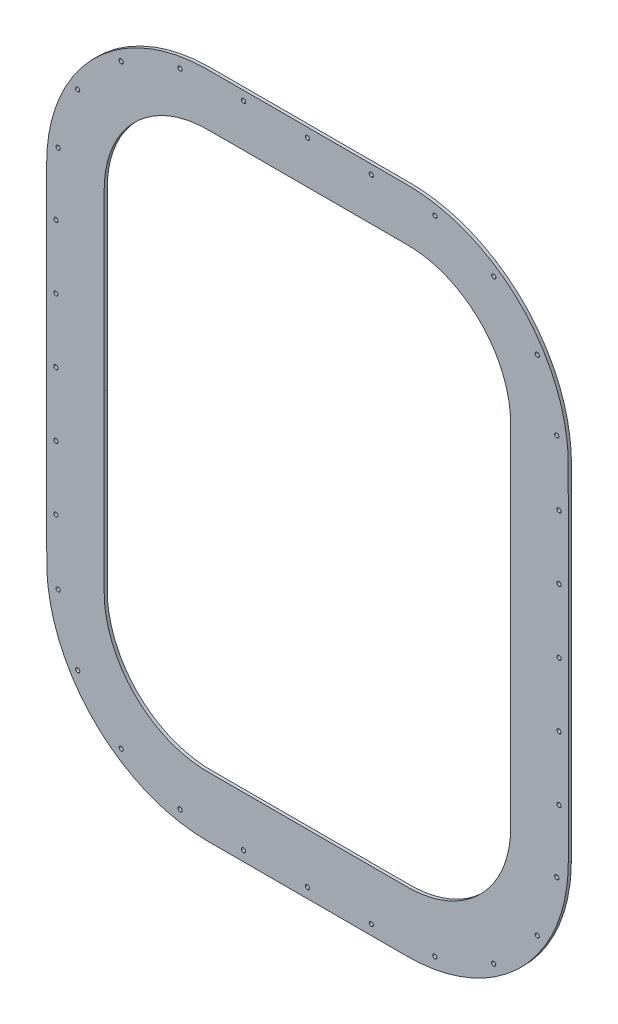
SolidWorks part; units mm, degrees
material "Сталь 3 ГОСТ 535-88"
ref_plane "Спереди" through (0, 0, 0) normal (0, 0, 1) x (1, 0, 0)
ref_plane "Сверху" through (0, 0, 0) normal (0, 1, 0) x (1, 0, 0)
ref_plane "Справа" through (0, 0, 0) normal (1, 0, 0) x (0, 0, -1)
sketch "Model" plane through (0, 0, 0) normal (0, 0, 1) x (1, 0, 0)
  spline S0 degree 3 poles (686.799, 219.4351) (686.8015, 233.7108) (686.7998, 247.9865) (686.7997, 276.538) (686.8001, 290.8137) (686.8001, 333.6409) (686.8, 362.1924) (686.8, 447.8467) (686.8, 504.9496) (686.8, 590.6192) (686.8, 619.1859) (686.8, 654.8942) (686.8031, 662.0359) (686.7984, 670.963) (686.7772, 672.7483) (686.6859, 676.3179) (686.6176, 678.1016) (686.3445, 683.4508) (686.0721, 687.0068) (684.2566, 704.7686) (681.3622, 718.7938) (672.7865, 746.0434) (667.1263, 759.1999) (653.2412, 784.1667) (645.0502, 795.9162) (626.4244, 817.5797) (616.051, 827.4251) (593.4407, 844.8927) (581.2722, 852.4548) (555.5632, 865.0005) (542.0668, 869.9511) (514.3076, 877.0039) (500.0892, 879.0962) (483.9931, 879.7895) (482.1463, 879.844) (478.691, 879.9047) (477.6323, 879.9057) (472.8047, 879.9051) (468.9033, 879.9055) (458.1634, 879.9055) (451.0035, 879.9055) (429.5236, 879.9055) (415.2037, 879.9055) (343.6042, 879.9055) (286.3245, 879.9057) (225.4722, 879.9053) (221.8995, 879.9052) (217.4336, 879.9052) (216.5404, 879.9081) (214.754, 879.8967) (213.8609, 879.8868) (211.1818, 879.8376) (209.3968, 879.7818) (200.4734, 879.3883) (193.3624, 878.7075) (172.1561, 875.5723) (158.2907, 872.0411) (131.4585, 862.1954) (118.6004, 855.9213) (94.3223, 840.8413) (82.9733, 832.0742) (62.2448, 812.4008) (52.9194, 801.5528) (36.5772, 778.11) (29.6245, 765.6091) (18.3314, 739.3598) (14.0339, 725.7079) (8.2593, 697.7226) (6.7982, 683.4477) (6.8, 669.1598) knots 1370.973405 1370.973405 1370.973405 1370.973405 1413.740122 1413.740122 1456.506838 1456.506838 1542.040272 1542.040272 1713.107139 1713.107139 1798.686145 1798.686145 1820.080897 1820.080897 1825.429585 1825.429585 1830.778273 1830.778273 1841.475649 1841.475649 1884.265152 1884.265152 1927.054655 1927.054655 1969.844159 1969.844159 2012.633662 2012.633662 2055.423165 2055.423165 2098.311408 2098.311408 2141.19965 2141.19965 2146.56068 2146.56068 2151.92171 2151.92171 2162.643771 2162.643771 2184.087892 2184.087892 2226.976134 2226.976134 2398.529103 2398.529103 2409.229434 2409.229434 2411.904516 2411.904516 2414.579599 2414.579599 2419.929764 2419.929764 2441.330424 2441.330424 2484.131745 2484.131745 2526.933066 2526.933066 2569.734386 2569.734386 2612.535707 2612.535707 2655.337028 2655.337028 2698.138349 2698.138349 2740.939669 2740.939669 2740.939669 2740.939669
  spline S1 degree 3 poles (6.8, 669.1598) (6.8, 554.954) (6.8, 440.7482) (6.8, 297.972) (6.8, 269.4017) (6.8, 237.26) (6.8, 233.6888) (6.8, 226.5462) (6.7988, 222.9747) (6.8026, 212.2613) (7.1617, 205.164) (9.3357, 183.8461) (12.2333, 169.7902) (20.8083, 142.5359) (26.4699, 129.3715) (36.8868, 110.6446) (40.6512, 104.6162) (48.8216, 92.8964) (53.1762, 87.2796) (67.1477, 71.029) (77.5232, 61.1824) (100.1392, 43.7149) (112.3204, 36.1477) (138.0408, 23.6044) (151.5435, 18.6552) (172.3727, 13.3683) (179.3623, 11.9714) (193.5364, 9.8881) (200.6319, 9.2149) (209.5782, 8.8278) (211.423, 8.7729) (214.887, 8.7115) (215.9044, 8.7107) (220.6306, 8.7119) (224.5877, 8.7112) (235.3325, 8.7112) (242.4957, 8.7111) (263.9853, 8.7111) (278.3117, 8.7111) (349.9438, 8.7112) (407.2494, 8.7111) (468.1373, 8.7112) (471.7389, 8.7113) (477.083, 8.7112) (478.2131, 8.7089) (481.4412, 8.7566) (483.3653, 8.8063) (492.3136, 9.1648) (499.4157, 9.8165) (513.5935, 11.855) (520.5935, 13.2309) (534.4875, 16.7129) (541.3096, 18.799) (561.5076, 26.125) (574.4387, 32.3811) (598.8267, 47.4238) (610.2201, 56.1755) (631.0536, 75.8455) (640.4448, 86.7245) (656.8705, 110.1985) (663.8805, 122.7636) (675.224, 149.072) (679.5476, 162.7829) (683.8928, 183.8251) (684.9779, 190.8681) (686.0714, 201.5552) (686.3445, 205.1215) (686.6183, 210.4861) (686.6868, 212.2748) (686.7781, 215.8547) (686.7987, 217.6446) (686.799, 219.4351) knots 0 0 0 0 342.110544 342.110544 427.694748 427.694748 438.392773 438.392773 449.090799 449.090799 470.48685 470.48685 513.278952 513.278952 556.071054 556.071054 577.467105 577.467105 598.863156 598.863156 641.655258 641.655258 684.44736 684.44736 727.351485 727.351485 748.803548 748.803548 770.25561 770.25561 775.618626 775.618626 780.981642 780.981642 791.707673 791.707673 813.159736 813.159736 856.063861 856.063861 1027.680361 1027.680361 1038.408269 1038.408269 1043.772223 1043.772223 1049.136177 1049.136177 1070.591992 1070.591992 1092.047807 1092.047807 1113.503622 1113.503622 1156.415253 1156.415253 1199.326883 1199.326883 1242.238514 1242.238514 1285.150144 1285.150144 1328.061775 1328.061775 1349.51759 1349.51759 1360.245497 1360.245497 1365.609451 1365.609451 1370.973405 1370.973405 1370.973405 1370.973405
  spline S2 degree 3 poles (611.8, 449.6949) (611.8, 402.1791) (611.8, 354.6634) (611.8, 283.3897) (611.8, 259.6319) (611.8, 232.9043) (611.8002, 229.9345) (611.7999, 225.4799) (611.8005, 223.9711) (611.7999, 221.0539) (611.7874, 219.8135) (611.5749, 212.401) (611.0155, 206.4829) (608.1729, 188.8911) (604.7349, 177.4448) (594.9606, 155.786) (588.6331, 145.6039) (577.3273, 131.8275) (573.2667, 127.4953) (564.5829, 119.3849) (559.9596, 115.6052) (550.2827, 108.7093) (545.2167, 105.5808) (534.7169, 100.0186) (529.297, 97.5903) (512.5842, 91.393) (500.9193, 88.7413) (486.1267, 87.389) (483.1216, 87.2163) (478.736, 87.106) (477.5663, 87.099) (474.6472, 87.101) (473.1376, 87.1002) (465.7105, 87.1009) (459.7689, 87.1004) (441.944, 87.1002) (430.0608, 87.1004) (394.411, 87.1004) (370.6445, 87.1004) (323.1405, 87.1004) (299.4031, 87.1004) (263.7969, 87.1004) (251.9282, 87.1003) (234.1251, 87.1003) (228.1907, 87.1003) (220.7727, 87.1006) (219.2891, 87.1007) (217.0638, 87.1006) (216.322, 87.0984) (214.8384, 87.1134) (214.0967, 87.1253) (210.3888, 87.2203) (207.4327, 87.3932) (192.658, 88.7484) (181.014, 91.3926) (164.321, 97.5832) (158.8788, 100.0193) (148.3902, 105.5752) (143.3088, 108.714) (133.6452, 115.6047) (129.0365, 119.3719) (120.3609, 127.4691) (116.333, 131.7567) (108.795, 140.9232) (105.3249, 145.7586) (99.0551, 155.8344) (96.2604, 161.0651) (91.3703, 171.8782) (89.2791, 177.4521) (85.8495, 188.813) (84.5146, 194.5913) (82.6044, 206.3037) (82.0376, 212.2069) (81.8384, 218.8791) (81.8224, 219.6206) (81.8022, 221.1038) (81.8, 221.8454) (81.7999, 224.0704) (81.8, 225.5538) (81.8, 230.0038) (81.8, 232.9704) (81.8, 259.6704) (81.8, 283.4037) (81.8, 354.6037) (81.8, 402.0704) (81.8, 449.537) knots 1139.240407 1139.240407 1139.240407 1139.240407 1281.689862 1281.689862 1352.91459 1352.91459 1361.817681 1361.817681 1366.269227 1366.269227 1370.720772 1370.720772 1388.526954 1388.526954 1424.139318 1424.139318 1459.754337 1459.754337 1477.561846 1477.561846 1495.369355 1495.369355 1513.176865 1513.176865 1530.984374 1530.984374 1566.599393 1566.599393 1575.503147 1575.503147 1579.955025 1579.955025 1584.406902 1584.406902 1602.214411 1602.214411 1637.82943 1637.82943 1709.059467 1709.059467 1780.202437 1780.202437 1815.773922 1815.773922 1833.559664 1833.559664 1838.0061 1838.0061 1840.229318 1840.229318 1842.452536 1842.452536 1851.345407 1851.345407 1886.916892 1886.916892 1904.702634 1904.702634 1922.488376 1922.488376 1940.274119 1940.274119 1958.059861 1958.059861 1975.845604 1975.845604 1993.631346 1993.631346 2011.418035 2011.418035 2029.204723 2029.204723 2046.991411 2046.991411 2049.214747 2049.214747 2051.438083 2051.438083 2055.884756 2055.884756 2064.7781 2064.7781 2135.924853 2135.924853 2278.218361 2278.218361 2278.218361 2278.218361
  spline S3 degree 3 poles (81.8, 449.537) (81.8, 497.0024) (81.8, 544.4677) (81.8, 615.6658) (81.8, 639.3984) (81.8004, 666.0977) (81.8004, 669.0643) (81.8005, 673.5142) (81.8005, 674.9975) (81.8006, 677.2224) (81.8012, 677.964) (81.8203, 679.4473) (81.8358, 680.1887) (82.0294, 686.861) (82.5902, 692.7647) (84.4885, 704.479) (85.8211, 710.2718) (89.2377, 721.6368) (91.3203, 727.206) (96.1983, 738.0263) (98.9631, 743.2205) (105.2186, 753.3084) (108.681, 758.1494) (116.207, 767.3302) (120.2288, 771.6263) (128.8938, 779.7393) (133.4824, 783.5017) (143.1367, 790.4099) (148.2111, 793.5564) (158.6942, 799.131) (164.1188, 801.5704) (180.8065, 807.7908) (192.4502, 810.4552) (207.227, 811.8336) (210.1839, 812.0112) (213.8927, 812.1115) (214.6346, 812.1255) (216.1187, 812.1414) (216.8607, 812.1413) (219.0869, 812.1412) (220.571, 812.1412) (227.9915, 812.1411) (233.928, 812.1411) (251.7373, 812.141) (263.6101, 812.141) (299.2287, 812.141) (322.9744, 812.1411) (370.5224, 812.1411) (394.3247, 812.1411) (430.0282, 812.1409) (441.9293, 812.1407) (459.781, 812.1404) (465.7316, 812.1403) (473.1698, 812.1402) (474.7347, 812.1401) (477.5319, 812.1401) (478.4557, 812.1393) (481.2633, 812.0751) (482.8221, 812.0159) (485.7892, 811.8507) (487.2712, 811.7435) (500.6068, 810.5587) (512.2962, 807.9273) (534.6297, 799.6971) (545.2319, 794.1025) (559.7831, 783.7661) (564.4044, 780.0006) (573.1128, 771.8907) (577.1867, 767.558) (588.5268, 753.7753) (594.8669, 743.5994) (604.6698, 721.9473) (608.1231, 710.4972) (610.9886, 692.9289) (611.5575, 687.026) (611.76, 680.354) (611.7765, 679.6126) (611.7972, 678.1294) (611.7999, 677.3877) (611.7999, 675.1627) (611.8, 673.6793) (611.8001, 669.2293) (611.8, 666.2626) (611.7999, 639.5625) (611.8, 615.829) (611.8, 544.6287) (611.8, 497.1618) (611.8, 449.6949) knots 0 0 0 0 142.305934 142.305934 213.458901 213.458901 222.353021 222.353021 226.800082 226.800082 229.023612 229.023612 231.247142 231.247142 249.035384 249.035384 266.823626 266.823626 284.611867 284.611867 302.403875 302.403875 320.195883 320.195883 337.98789 337.98789 355.779898 355.779898 373.571905 373.571905 391.363913 391.363913 426.947928 426.947928 435.843932 435.843932 438.067933 438.067933 440.291934 440.291934 444.739935 444.739935 462.531943 462.531943 498.115958 498.115958 569.283988 569.283988 640.621573 640.621573 676.290365 676.290365 694.124761 694.124761 698.58336 698.58336 703.041959 703.041959 707.500558 707.500558 711.959157 711.959157 747.627949 747.627949 783.296741 783.296741 801.131137 801.131137 818.965533 818.965533 854.634325 854.634325 890.210085 890.210085 907.997965 907.997965 910.22145 910.22145 912.444935 912.444935 916.891905 916.891905 925.785846 925.785846 996.937366 996.937366 1139.240407 1139.240407 1139.240407 1139.240407
  spline S4 degree 3 poles (21.7729, 192.7533) (21.4109, 192.751) (21.0511, 192.8298) (20.3851, 193.1021) (20.0838, 193.3065) (19.5711, 193.8126) (19.3722, 194.1228) (19.094, 194.786) (19.0251, 195.144) (19.0209, 195.8644) (19.1004, 196.2243) (19.3728, 196.8897) (19.5765, 197.1919) (20.083, 197.7047) (20.393, 197.9033) (21.0567, 198.1817) (21.4142, 198.2499) (21.773, 198.2522) knots -8.655349 -8.655349 -8.655349 -8.655349 -7.58771 -7.58771 -6.520071 -6.520071 -5.443135 -5.443135 -4.3662 -4.3662 -3.279574 -3.279574 -2.192949 -2.192949 -1.096474 -1.096474 0 0 0 0
  spline S5 degree 3 poles (21.773, 198.2522) (22.1318, 198.2499) (22.4893, 198.1815) (23.153, 197.9031) (23.4629, 197.7046) (23.9697, 197.1917) (24.1738, 196.8906) (24.4466, 196.2243) (24.525, 195.865) (24.5209, 195.1445) (24.4519, 194.7864) (24.1739, 194.1234) (23.975, 193.8128) (23.1985, 193.0462) (22.5024, 192.758) (21.7729, 192.7533) knots -17.268882 -17.268882 -17.268882 -17.268882 -16.182392 -16.182392 -15.095902 -15.095902 -14.018376 -14.018376 -12.94085 -12.94085 -11.873927 -11.873927 -10.807005 -10.807005 -8.655349 -8.655349 -8.655349 -8.655349
  spline S6 degree 3 poles (18.8009, 275.8275) (18.439, 275.8252) (18.0791, 275.9041) (17.4131, 276.1763) (17.1118, 276.3807) (16.3508, 277.1318) (16.0464, 277.8661) (16.0533, 278.9351) (16.1228, 279.293) (16.4009, 279.9556) (16.5992, 280.267) (17.3784, 281.0361) (18.0678, 281.3214) (18.801, 281.3261) knots -8.615956 -8.615956 -8.615956 -8.615956 -7.539826 -7.539826 -6.463697 -6.463697 -4.331196 -4.331196 -3.255511 -3.255511 -2.179826 -2.179826 0 0 0 0
  spline S7 degree 3 poles (18.801, 281.3261) (19.5338, 281.3214) (20.2238, 281.0358) (21.2511, 280.0219) (21.5554, 279.2875) (21.5487, 278.2184) (21.4802, 277.8608) (21.2018, 277.1974) (21.0032, 276.8871) (20.2265, 276.1204) (19.5303, 275.8322) (18.8009, 275.8275) knots -17.268228 -17.268228 -17.268228 -17.268228 -15.069566 -15.069566 -12.937355 -12.937355 -11.861029 -11.861029 -10.784704 -10.784704 -8.615956 -8.615956 -8.615956 -8.615956
  spline S8 degree 3 poles (18.801, 359.013) (18.4391, 359.0107) (18.0792, 359.0895) (17.4133, 359.3617) (17.1119, 359.566) (16.3509, 360.3172) (16.0465, 361.0512) (16.0533, 362.1203) (16.1229, 362.4781) (16.401, 363.1408) (16.5993, 363.452) (17.3785, 364.221) (18.068, 364.5063) (18.801, 364.511) knots -8.61561 -8.61561 -8.61561 -8.61561 -7.539572 -7.539572 -6.463533 -6.463533 -4.330995 -4.330995 -3.255301 -3.255301 -2.179607 -2.179607 0 0 0 0
  spline S9 degree 3 poles (18.801, 364.511) (19.5337, 364.5063) (20.2239, 364.2207) (21.2511, 363.2069) (21.5555, 362.4727) (21.5488, 361.4035) (21.4802, 361.0461) (21.2018, 360.3826) (21.0032, 360.0725) (20.2266, 359.3058) (19.5303, 359.0177) (18.801, 359.013) knots -17.267373 -17.267373 -17.267373 -17.267373 -15.068966 -15.068966 -12.936767 -12.936767 -11.860422 -11.860422 -10.784077 -10.784077 -8.61561 -8.61561 -8.61561 -8.61561
  spline S10 degree 3 poles (18.8011, 442.1825) (18.0682, 442.1872) (17.3785, 442.4726) (16.351, 443.4864) (16.0466, 444.2205) (16.0534, 445.2895) (16.123, 445.6473) (16.4011, 446.3099) (16.5994, 446.6211) (17.3787, 447.3901) (18.068, 447.6753) (18.8011, 447.68) knots -8.57834 -8.57834 -8.57834 -8.57834 -6.40068 -6.40068 -4.288939 -4.288939 -3.223755 -3.223755 -2.15857 -2.15857 0 0 0 0
  spline S11 degree 3 poles (18.8011, 447.68) (19.5339, 447.6753) (20.2238, 447.3898) (21.2512, 446.3761) (21.5556, 445.6418) (21.5489, 444.5728) (21.4803, 444.2153) (21.2019, 443.552) (21.0033, 443.2418) (20.4906, 442.7358) (20.1882, 442.532) (19.5232, 442.2602) (19.1627, 442.1802) (18.8011, 442.1825) knots -17.266593 -17.266593 -17.266593 -17.266593 -15.049111 -15.049111 -12.898663 -12.898663 -11.813153 -11.813153 -10.727642 -10.727642 -9.652991 -9.652991 -8.57834 -8.57834 -8.57834 -8.57834
  spline S12 degree 3 poles (18.8011, 525.3396) (18.4392, 525.3372) (18.0795, 525.416) (17.4135, 525.6881) (17.1122, 525.8924) (16.3512, 526.6433) (16.0467, 527.3773) (16.0535, 528.4462) (16.1231, 528.8041) (16.4012, 529.4666) (16.5995, 529.7778) (17.3789, 530.5467) (18.0682, 530.8318) (18.8012, 530.8365) knots -8.614653 -8.614653 -8.614653 -8.614653 -7.538656 -7.538656 -6.46266 -6.46266 -4.330465 -4.330465 -3.254973 -3.254973 -2.179481 -2.179481 0 0 0 0
  spline S13 degree 3 poles (18.8012, 530.8365) (19.5339, 530.8318) (20.2238, 530.5463) (21.2512, 529.5329) (21.5557, 528.7986) (21.549, 527.7296) (21.4804, 527.3721) (21.202, 526.7089) (21.0033, 526.3987) (20.2265, 525.6323) (19.5305, 525.3442) (18.8011, 525.3396) knots -17.265728 -17.265728 -17.265728 -17.265728 -15.067308 -15.067308 -12.935376 -12.935376 -11.859227 -11.859227 -10.783078 -10.783078 -8.614653 -8.614653 -8.614653 -8.614653
  spline S14 degree 3 poles (18.8012, 608.5003) (18.0683, 608.505) (17.3785, 608.7906) (16.3511, 609.8046) (16.0468, 610.5387) (16.0536, 611.6078) (16.1232, 611.9657) (16.4012, 612.6283) (16.5995, 612.9396) (17.3788, 613.7087) (18.0681, 613.994) (18.8013, 613.9987) knots -8.579119 -8.579119 -8.579119 -8.579119 -6.401297 -6.401297 -4.28937 -4.28937 -3.224073 -3.224073 -2.158776 -2.158776 0 0 0 0
  spline S15 degree 3 poles (18.8013, 613.9987) (19.5341, 613.994) (20.2241, 613.7084) (21.2514, 612.6945) (21.5558, 611.9602) (21.549, 610.891) (21.4805, 610.5335) (21.2021, 609.8701) (21.0035, 609.5599) (20.4908, 609.0538) (20.1884, 608.8499) (19.5234, 608.5781) (19.1629, 608.498) (18.8012, 608.5003) knots -17.267899 -17.267899 -17.267899 -17.267899 -15.050311 -15.050311 -12.89974 -12.89974 -11.814148 -11.814148 -10.728555 -10.728555 -9.653837 -9.653837 -8.579119 -8.579119 -8.579119 -8.579119
  spline S16 degree 3 poles (47.2061, 769.9366) (46.4732, 769.9413) (45.7834, 770.2268) (44.756, 771.2406) (44.4516, 771.9747) (44.4584, 773.0436) (44.528, 773.4015) (44.8061, 774.064) (45.0044, 774.3753) (45.7837, 775.1442) (46.473, 775.4295) (47.2061, 775.4341) knots -8.578351 -8.578351 -8.578351 -8.578351 -6.400695 -6.400695 -4.288948 -4.288948 -3.223763 -3.223763 -2.158577 -2.158577 0 0 0 0
  spline S17 degree 3 poles (47.2061, 775.4341) (47.9389, 775.4295) (48.6288, 775.1439) (49.6562, 774.1303) (49.9606, 773.396) (49.9539, 772.327) (49.8853, 771.9695) (49.6069, 771.3062) (49.4083, 770.9959) (48.8956, 770.49) (48.5932, 770.2862) (47.9282, 770.0143) (47.5677, 769.9343) (47.2061, 769.9366) knots -17.26661 -17.26661 -17.26661 -17.26661 -15.049124 -15.049124 -12.898678 -12.898678 -11.813165 -11.813165 -10.727653 -10.727653 -9.653002 -9.653002 -8.578351 -8.578351 -8.578351 -8.578351
  spline S18 degree 3 poles (21.7465, 691.5084) (21.3845, 691.5111) (21.026, 691.5946) (20.3636, 691.8759) (20.0652, 692.0842) (19.3142, 692.8457) (19.02, 693.5837) (19.0412, 694.6526) (19.1158, 695.0096) (19.4028, 695.6682) (19.6053, 695.9769) (20.3949, 696.7352) (21.0881, 697.0111) (21.8212, 697.0058) knots -8.6173 -8.6173 -8.6173 -8.6173 -7.540795 -7.540795 -6.464289 -6.464289 -4.331359 -4.331359 -3.255758 -3.255758 -2.180156 -2.180156 0 0 0 0
  spline S19 degree 3 poles (21.8212, 697.0058) (22.5538, 696.9912) (23.2399, 696.6962) (24.2533, 695.6687) (24.5477, 694.9303) (24.5265, 693.8611) (24.4531, 693.505) (24.1656, 692.845) (23.9629, 692.538) (23.1765, 691.782) (22.4752, 691.503) (21.7465, 691.5084) knots -17.267222 -17.267222 -17.267222 -17.267222 -15.069294 -15.069294 -12.937813 -12.937813 -11.861075 -11.861075 -10.784337 -10.784337 -8.6173 -8.6173 -8.6173 -8.6173
  spline S20 degree 3 poles (103.921, 830.0783) (103.2021, 830.0762) (102.4839, 830.3765) (101.4654, 831.3962) (101.1722, 832.1025) (101.1705, 833.5449) (101.4688, 834.263) (102.4948, 835.2874) (103.192, 835.5712) (103.9211, 835.5758) knots -8.656254 -8.656254 -8.656254 -8.656254 -6.507829 -6.507829 -4.341708 -4.341708 -2.190884 -2.190884 0 0 0 0
  spline S21 degree 3 poles (103.9211, 835.5758) (104.2815, 835.5735) (104.6382, 835.5041) (105.3009, 835.2285) (105.6116, 835.0246) (106.3761, 834.2619) (106.6701, 833.5494) (106.6708, 832.1068) (106.3761, 831.393) (105.3546, 830.3735) (104.6423, 830.0803) (103.921, 830.0783) knots -17.26611 -17.26611 -17.26611 -17.26611 -16.186211 -16.186211 -15.120123 -15.120123 -12.964169 -12.964169 -10.812053 -10.812053 -8.656254 -8.656254 -8.656254 -8.656254
  spline S22 degree 3 poles (180.6315, 860.3228) (179.9123, 860.3234) (179.1962, 860.6192) (178.1761, 861.6401) (177.8817, 862.3476) (177.8815, 863.7916) (178.1793, 864.507) (178.9425, 865.2699) (179.2415, 865.4676) (179.9179, 865.7488) (180.2582, 865.8178) (180.6315, 865.8202) knots -8.652907 -8.652907 -8.652907 -8.652907 -6.502807 -6.502807 -4.341051 -4.341051 -2.191212 -2.191212 -1.116837 -1.116837 0 0 0 0
  spline S23 degree 3 poles (180.6315, 865.8202) (180.9918, 865.8179) (181.3484, 865.7486) (182.0116, 865.4726) (182.3219, 865.2695) (183.0863, 864.5059) (183.3807, 863.7938) (183.3816, 862.3528) (183.0864, 861.637) (182.3245, 860.8773) (182.0151, 860.6726) (181.3576, 860.4006) (180.988, 860.3225) (180.6315, 860.3228) knots -17.265859 -17.265859 -17.265859 -17.265859 -16.18123 -16.18123 -15.107711 -15.107711 -12.942775 -12.942775 -10.786622 -10.786622 -9.718808 -9.718808 -8.652907 -8.652907 -8.652907 -8.652907
  spline S24 degree 3 poles (263.5412, 865.1091) (262.8199, 865.1072) (262.1063, 865.4042) (261.3341, 866.1753) (261.1448, 866.4627) (260.86, 867.1479) (260.7908, 867.4862) (260.7901, 868.577) (261.0875, 869.2933) (261.8566, 870.0616) (262.1674, 870.2648) (262.8452, 870.5391) (263.1775, 870.6036) (263.5401, 870.6059) knots -8.669528 -8.669528 -8.669528 -8.669528 -6.527716 -6.527716 -5.424883 -5.424883 -4.317514 -4.317514 -2.1792 -2.1792 -1.081624 -1.081624 0 0 0 0
  spline S25 degree 3 poles (263.5401, 870.6059) (263.914, 870.6035) (264.2549, 870.5353) (264.9391, 870.2492) (265.2242, 870.0602) (265.9977, 869.2905) (266.288, 868.5783) (266.2916, 867.1365) (265.9935, 866.4221) (264.9753, 865.406) (264.2592, 865.1109) (263.5412, 865.1091) knots -17.26582 -17.26582 -17.26582 -17.26582 -16.159648 -16.159648 -15.073432 -15.073432 -12.936863 -12.936863 -10.801787 -10.801787 -8.669528 -8.669528 -8.669528 -8.669528
  spline S26 degree 3 poles (346.8121, 870.5998) (347.5333, 870.5966) (348.245, 870.2989) (349.2594, 869.2759) (349.554, 868.559) (349.5463, 867.125) (349.2455, 866.4026) (348.2167, 865.3866) (347.5167, 865.1046) (346.7883, 865.103) knots -8.578876 -8.578876 -8.578876 -8.578876 -6.431908 -6.431908 -4.29221 -4.29221 -2.16845 -2.16845 0 0 0 0
  spline S27 degree 3 poles (346.7883, 865.103) (346.4275, 865.1069) (346.0739, 865.1768) (345.4063, 865.4591) (345.1041, 865.6563) (344.5881, 866.1794) (344.3982, 866.4662) (344.1211, 867.145) (344.0481, 867.4985) (344.055, 868.5851) (344.3485, 869.294) (345.3769, 870.3093) (346.0904, 870.603) (346.8121, 870.5998) knots -17.26582 -17.26582 -17.26582 -17.26582 -16.176818 -16.176818 -15.083294 -15.083294 -13.973746 -13.973746 -12.885723 -12.885723 -10.72689 -10.72689 -8.578876 -8.578876 -8.578876 -8.578876
  spline S28 degree 3 poles (430.059, 870.6063) (430.7774, 870.6073) (431.4964, 870.3086) (432.5168, 869.2874) (432.8087, 868.5845) (432.8102, 867.1405) (432.5123, 866.421) (431.4889, 865.3985) (430.7856, 865.1135) (430.0599, 865.1089) knots -8.634779 -8.634779 -8.634779 -8.634779 -6.489992 -6.489992 -4.321534 -4.321534 -2.176713 -2.176713 0 0 0 0
  spline S29 degree 3 poles (430.0599, 865.1089) (429.6928, 865.1113) (429.357, 865.1776) (428.6817, 865.4541) (428.3715, 865.6576) (427.6048, 866.4241) (427.3106, 867.1363) (427.3098, 868.5777) (427.6049, 869.2919) (428.6236, 870.3084) (429.3407, 870.6053) (430.059, 870.6063) knots -17.265821 -17.265821 -17.265821 -17.265821 -16.167502 -16.167502 -15.084346 -15.084346 -12.931086 -12.931086 -10.779533 -10.779533 -8.634779 -8.634779 -8.634779 -8.634779
  spline S30 degree 3 poles (512.9685, 865.8204) (513.6948, 865.8195) (514.3989, 865.5271) (515.424, 864.5041) (515.7183, 863.7948) (515.7183, 862.3567) (515.4212, 861.6356) (514.3987, 860.6143) (513.6946, 860.3278) (512.9685, 860.3232) knots -8.620815 -8.620815 -8.620815 -8.620815 -6.456517 -6.456517 -4.303944 -4.303944 -2.170065 -2.170065 0 0 0 0
  spline S31 degree 3 poles (512.9685, 860.3232) (512.5989, 860.3255) (512.2613, 860.3913) (511.5834, 860.6736) (511.2822, 860.8695) (510.5136, 861.6409) (510.2183, 862.3472) (510.2189, 863.7904) (510.5145, 864.5073) (511.53, 865.5217) (512.2516, 865.8212) (512.9685, 865.8204) knots -17.26586 -17.26586 -17.26586 -17.26586 -16.155554 -16.155554 -15.063784 -15.063784 -12.900652 -12.900652 -10.756985 -10.756985 -8.620815 -8.620815 -8.620815 -8.620815
  spline S32 degree 3 poles (589.679, 835.5758) (590.4118, 835.5711) (591.1015, 835.2857) (592.129, 834.272) (592.4335, 833.5379) (592.4266, 832.469) (592.357, 832.1111) (592.0789, 831.4486) (591.8806, 831.1374) (591.1013, 830.3685) (590.412, 830.0833) (589.6789, 830.0786) knots -8.578041 -8.578041 -8.578041 -8.578041 -6.4004 -6.4004 -4.288731 -4.288731 -3.223581 -3.223581 -2.158432 -2.158432 0 0 0 0
  spline S33 degree 3 poles (589.6789, 830.0786) (588.9462, 830.0833) (588.2562, 830.3688) (587.2289, 831.3823) (586.9245, 832.1166) (586.9312, 833.1856) (586.9997, 833.5431) (587.2782, 834.2064) (587.4768, 834.5166) (587.9895, 835.0225) (588.2919, 835.2263) (588.9569, 835.4981) (589.3174, 835.5781) (589.679, 835.5758) knots -17.26611 -17.26611 -17.26611 -17.26611 -15.048705 -15.048705 -12.898259 -12.898259 -11.812761 -11.812761 -10.727262 -10.727262 -9.652652 -9.652652 -8.578041 -8.578041 -8.578041 -8.578041
  spline S34 degree 3 poles (646.394, 775.4345) (647.113, 775.4365) (647.8306, 775.1365) (648.8502, 774.1176) (649.1435, 773.4095) (649.1429, 771.9656) (648.8474, 771.2515) (647.8241, 770.2263) (647.1189, 769.9413) (646.3939, 769.9366) knots -8.654512 -8.654512 -8.654512 -8.654512 -6.505321 -6.505321 -4.33764 -4.33764 -2.181263 -2.181263 0 0 0 0
  spline S35 degree 3 poles (646.3939, 769.9366) (646.0334, 769.9389) (645.6767, 770.0084) (645.014, 770.284) (644.7033, 770.4879) (643.9389, 771.2506) (643.6448, 771.9632) (643.6441, 773.4059) (643.9389, 774.1196) (644.9604, 775.1393) (645.6726, 775.4325) (646.394, 775.4345) knots -17.266611 -17.266611 -17.266611 -17.266611 -16.18643 -16.18643 -15.120072 -15.120072 -12.963552 -12.963552 -10.810885 -10.810885 -8.654512 -8.654512 -8.654512 -8.654512
  spline S36 degree 3 poles (671.7789, 697.0058) (672.1408, 697.0129) (672.5015, 696.9392) (673.1713, 696.6759) (673.4751, 696.4758) (673.9948, 695.9767) (674.1979, 695.6693) (674.4852, 695.01) (674.5588, 694.6531) (674.5798, 693.5872) (674.2835, 692.8434) (673.2719, 691.8176) (672.5864, 691.523) (671.8535, 691.5084) knots -8.6526 -8.6526 -8.6526 -8.6526 -7.580202 -7.580202 -6.507805 -6.507805 -5.426131 -5.426131 -4.344457 -4.344457 -2.210458 -2.210458 0 0 0 0
  spline S37 degree 3 poles (671.8535, 691.5084) (671.1207, 691.5031) (670.4269, 691.7793) (669.3856, 692.7793) (669.0719, 693.5089) (669.0636, 694.5784) (669.1276, 694.9367) (669.3968, 695.604) (669.5914, 695.9165) (670.3568, 696.6935) (671.0503, 696.9914) (671.7789, 697.0058) knots -17.267223 -17.267223 -17.267223 -17.267223 -15.078909 -15.078909 -12.955429 -12.955429 -11.883421 -11.883421 -10.811413 -10.811413 -8.6526 -8.6526 -8.6526 -8.6526
  spline S38 degree 3 poles (674.7988, 613.9987) (675.5317, 613.994) (676.2215, 613.7084) (677.2489, 612.6944) (677.5532, 611.9603) (677.5464, 610.8912) (677.4768, 610.5333) (677.1988, 609.8707) (677.0005, 609.5594) (676.2212, 608.7903) (675.5318, 608.505) (674.7987, 608.5003) knots -8.5791 -8.5791 -8.5791 -8.5791 -6.401218 -6.401218 -4.289311 -4.289311 -3.224018 -3.224018 -2.158725 -2.158725 0 0 0 0
  spline S39 degree 3 poles (674.7987, 608.5003) (674.0659, 608.505) (673.3759, 608.7907) (672.3486, 609.8045) (672.0442, 610.5388) (672.051, 611.6079) (672.1195, 611.9655) (672.3979, 612.6289) (672.5965, 612.9391) (673.1092, 613.4452) (673.4116, 613.649) (674.0766, 613.9209) (674.4371, 614.001) (674.7988, 613.9987) knots -17.267899 -17.267899 -17.267899 -17.267899 -15.05033 -15.05033 -12.899729 -12.899729 -11.814125 -11.814125 -10.728521 -10.728521 -9.653811 -9.653811 -8.5791 -8.5791 -8.5791 -8.5791
  spline S40 degree 3 poles (674.7989, 530.8365) (675.5217, 530.836) (676.2303, 530.5423) (677.2516, 529.5251) (677.5493, 528.8073) (677.5472, 527.3645) (677.2543, 526.6572) (676.2286, 525.6288) (675.5238, 525.3442) (674.7988, 525.3396) knots -8.633629 -8.633629 -8.633629 -8.633629 -6.477943 -6.477943 -4.33302 -4.33302 -2.17353 -2.17353 0 0 0 0
  spline S41 degree 3 poles (674.7988, 525.3396) (674.0737, 525.3442) (673.3694, 525.6291) (672.3442, 526.6566) (672.0499, 527.3637) (672.0479, 528.8082) (672.3447, 529.5228) (673.3634, 530.5381) (674.0806, 530.8371) (674.7989, 530.8365) knots -17.265729 -17.265729 -17.265729 -17.265729 -15.089357 -15.089357 -12.929232 -12.929232 -10.776256 -10.776256 -8.633629 -8.633629 -8.633629 -8.633629
  spline S42 degree 3 poles (674.7989, 447.68) (675.5318, 447.6753) (676.2215, 447.3898) (677.249, 446.376) (677.5534, 445.6419) (677.5466, 444.573) (677.477, 444.2151) (677.1989, 443.5526) (677.0006, 443.2413) (676.2213, 442.4724) (675.5319, 442.1871) (674.7989, 442.1825) knots -8.578322 -8.578322 -8.578322 -8.578322 -6.400609 -6.400609 -4.288885 -4.288885 -3.223705 -3.223705 -2.158525 -2.158525 0 0 0 0
  spline S43 degree 3 poles (674.7989, 442.1825) (674.0661, 442.1871) (673.3762, 442.4727) (672.3488, 443.4863) (672.0444, 444.2206) (672.0511, 445.2896) (672.1197, 445.6471) (672.3981, 446.3104) (672.5967, 446.6207) (673.1094, 447.1266) (673.4118, 447.3304) (674.0768, 447.6023) (674.4373, 447.6823) (674.7989, 447.68) knots -17.266593 -17.266593 -17.266593 -17.266593 -15.049124 -15.049124 -12.898649 -12.898649 -11.813127 -11.813127 -10.727606 -10.727606 -9.652964 -9.652964 -8.578322 -8.578322 -8.578322 -8.578322
  spline S44 degree 3 poles (674.799, 364.511) (675.1609, 364.5133) (675.5208, 364.4345) (676.1867, 364.1623) (676.4881, 363.9579) (677.2491, 363.2068) (677.5535, 362.4728) (677.5467, 361.4037) (677.4771, 361.0459) (677.199, 360.3832) (677.0007, 360.072) (676.2215, 359.303) (675.532, 359.0177) (674.799, 359.013) knots -8.615613 -8.615613 -8.615613 -8.615613 -7.539574 -7.539574 -6.463535 -6.463535 -4.330989 -4.330989 -3.255288 -3.255288 -2.179587 -2.179587 0 0 0 0
  spline S45 degree 3 poles (674.799, 359.013) (674.0663, 359.0177) (673.3761, 359.3033) (672.3489, 360.3171) (672.0445, 361.0513) (672.0512, 362.1205) (672.1198, 362.4779) (672.3982, 363.1414) (672.5968, 363.4515) (673.3734, 364.2182) (674.0697, 364.5063) (674.799, 364.511) knots -17.267374 -17.267374 -17.267374 -17.267374 -15.068998 -15.068998 -12.936794 -12.936794 -11.860449 -11.860449 -10.784104 -10.784104 -8.615613 -8.615613 -8.615613 -8.615613
  spline S46 degree 3 poles (674.7991, 281.3261) (675.161, 281.3284) (675.5209, 281.2496) (676.1869, 280.9773) (676.4882, 280.7729) (677.2492, 280.0218) (677.5536, 279.2876) (677.5467, 278.2185) (677.4772, 277.8606) (677.1991, 277.198) (677.0008, 276.8867) (676.2216, 276.1176) (675.5322, 275.8322) (674.799, 275.8275) knots -8.615963 -8.615963 -8.615963 -8.615963 -7.53984 -7.53984 -6.463717 -6.463717 -4.331201 -4.331201 -3.255508 -3.255508 -2.179814 -2.179814 0 0 0 0
  spline S47 degree 3 poles (674.799, 275.8275) (674.0662, 275.8322) (673.3762, 276.1179) (672.3489, 277.1317) (672.0446, 277.8661) (672.0513, 278.9353) (672.1198, 279.2928) (672.3982, 279.9562) (672.5968, 280.2665) (673.3735, 281.0332) (674.0696, 281.3214) (674.7991, 281.3261) knots -17.268228 -17.268228 -17.268228 -17.268228 -15.069603 -15.069603 -12.937396 -12.937396 -11.861073 -11.861073 -10.78475 -10.78475 -8.615963 -8.615963 -8.615963 -8.615963
  spline S48 degree 3 poles (671.8271, 198.2522) (672.538, 198.2568) (673.272, 197.9526) (674.0238, 197.1917) (674.2279, 196.8907) (674.5006, 196.2244) (674.5791, 195.865) (674.5749, 195.1446) (674.5049, 194.7861) (674.2272, 194.1239) (674.0286, 193.8123) (673.2496, 193.0434) (672.5602, 192.758) (671.827, 192.7533) knots -8.654614 -8.654614 -8.654614 -8.654614 -6.503877 -6.503877 -5.417434 -5.417434 -4.330991 -4.330991 -3.255811 -3.255811 -2.180631 -2.180631 0 0 0 0
  spline S49 degree 3 poles (671.827, 192.7533) (671.0942, 192.758) (670.4042, 193.0437) (669.6252, 193.8125) (669.4263, 194.1229) (669.1481, 194.786) (669.0792, 195.144) (669.0749, 195.8646) (669.1534, 196.2239) (669.426, 196.8902) (669.6301, 197.1914) (670.1366, 197.7042) (670.4479, 197.9024) (671.1107, 198.1804) (671.4686, 198.2499) (671.8271, 198.2522) knots -17.268882 -17.268882 -17.268882 -17.268882 -15.1093 -15.1093 -14.043164 -14.043164 -12.977029 -12.977029 -11.900508 -11.900508 -10.823988 -10.823988 -9.739301 -9.739301 -8.654614 -8.654614 -8.654614 -8.654614
  spline S50 degree 3 poles (646.3339, 119.7398) (647.067, 119.7351) (647.7568, 119.4494) (648.7841, 118.4349) (649.0884, 117.7005) (649.0815, 116.6314) (649.012, 116.2734) (648.734, 115.6106) (648.5357, 115.2992) (647.7566, 114.5298) (647.0671, 114.2442) (646.3338, 114.2396) knots -8.580892 -8.580892 -8.580892 -8.580892 -6.402582 -6.402582 -4.290291 -4.290291 -3.224768 -3.224768 -2.159245 -2.159245 0 0 0 0
  spline S51 degree 3 poles (646.3338, 114.2396) (645.6009, 114.2442) (644.9108, 114.5301) (643.8836, 115.5443) (643.5794, 116.2789) (643.5861, 117.3482) (643.6546, 117.7058) (643.9329, 118.3693) (644.1315, 118.6797) (644.6441, 119.186) (644.9465, 119.39) (645.6116, 119.662) (645.9722, 119.7421) (646.3339, 119.7398) knots -17.27094 -17.27094 -17.27094 -17.27094 -15.053064 -15.053064 -12.902213 -12.902213 -11.816441 -11.816441 -10.73067 -10.73067 -9.655781 -9.655781 -8.580892 -8.580892 -8.580892 -8.580892
  spline S52 degree 3 poles (589.5863, 59.5917) (589.9483, 59.5941) (590.3082, 59.5152) (590.9742, 59.2428) (591.2755, 59.0383) (592.0365, 58.2868) (592.3407, 57.5524) (592.3339, 56.4832) (592.2644, 56.1253) (591.9864, 55.4625) (591.7881, 55.151) (591.0089, 54.3816) (590.3195, 54.0961) (589.5862, 54.0914) knots -8.617439 -8.617439 -8.617439 -8.617439 -7.54115 -7.54115 -6.46486 -6.46486 -4.332031 -4.332031 -3.256143 -3.256143 -2.180255 -2.180255 0 0 0 0
  spline S53 degree 3 poles (589.5862, 54.0914) (588.8532, 54.0961) (588.1632, 54.3819) (587.136, 55.3962) (586.8317, 56.1308) (586.8385, 57.2001) (586.907, 57.5577) (587.1853, 58.2212) (587.3839, 58.5316) (588.1605, 59.2986) (588.8566, 59.587) (589.5863, 59.5917) knots -17.271088 -17.271088 -17.271088 -17.271088 -15.07213 -15.07213 -12.939641 -12.939641 -11.863138 -11.863138 -10.786636 -10.786636 -8.617439 -8.617439 -8.617439 -8.617439
  spline S54 degree 3 poles (512.8589, 29.3966) (513.2209, 29.399) (513.5808, 29.3201) (514.2468, 29.0477) (514.5481, 28.8431) (515.3091, 28.0917) (515.6134, 27.3573) (515.6065, 26.2881) (515.537, 25.9301) (515.259, 25.2673) (515.0607, 24.9559) (514.2816, 24.1864) (513.5921, 23.9008) (512.8588, 23.8962) knots -8.617537 -8.617537 -8.617537 -8.617537 -7.541245 -7.541245 -6.464952 -6.464952 -4.332083 -4.332083 -3.256173 -3.256173 -2.180262 -2.180262 0 0 0 0
  spline S55 degree 3 poles (512.8588, 23.8962) (512.1258, 23.9008) (511.4358, 24.1867) (510.4086, 25.201) (510.1044, 25.9356) (510.1111, 27.0049) (510.1796, 27.3625) (510.4579, 28.0261) (510.6565, 28.3365) (511.4331, 29.1035) (512.1293, 29.3919) (512.8589, 29.3966) knots -17.271261 -17.271261 -17.271261 -17.271261 -15.072307 -15.072307 -12.939786 -12.939786 -11.863261 -11.863261 -10.786736 -10.786736 -8.617537 -8.617537 -8.617537 -8.617537
  spline S56 degree 3 poles (430.06, 24.6111) (430.422, 24.6134) (430.782, 24.5345) (431.448, 24.2621) (431.7493, 24.0576) (432.5102, 23.3061) (432.8145, 22.5717) (432.8077, 21.5025) (432.7381, 21.1446) (432.4601, 20.4818) (432.2619, 20.1703) (431.4827, 19.4009) (430.7933, 19.1153) (430.06, 19.1106) knots -8.617555 -8.617555 -8.617555 -8.617555 -7.541264 -7.541264 -6.464972 -6.464972 -4.332093 -4.332093 -3.256177 -3.256177 -2.180261 -2.180261 0 0 0 0
  spline S57 degree 3 poles (430.06, 19.1106) (429.327, 19.1153) (428.6369, 19.4012) (427.6097, 20.4155) (427.3055, 21.1501) (427.3122, 22.2194) (427.3807, 22.577) (427.659, 23.2406) (427.8576, 23.5509) (428.6342, 24.318) (429.3304, 24.6064) (430.06, 24.6111) knots -17.271292 -17.271292 -17.271292 -17.271292 -15.072342 -15.072342 -12.939813 -12.939813 -11.863283 -11.863283 -10.786752 -10.786752 -8.617555 -8.617555 -8.617555 -8.617555
  spline S58 degree 3 poles (346.8001, 24.6155) (347.1621, 24.6178) (347.522, 24.5389) (348.188, 24.2665) (348.4893, 24.062) (349.2503, 23.3105) (349.5545, 22.5761) (349.5477, 21.5069) (349.4782, 21.149) (349.2002, 20.4862) (349.0019, 20.1747) (348.2228, 19.4053) (347.5333, 19.1197) (346.8, 19.115) knots -8.617555 -8.617555 -8.617555 -8.617555 -7.541264 -7.541264 -6.464972 -6.464972 -4.332093 -4.332093 -3.256177 -3.256177 -2.180261 -2.180261 0 0 0 0
  spline S59 degree 3 poles (346.8, 19.115) (346.067, 19.1197) (345.377, 19.4056) (344.3498, 20.4199) (344.0455, 21.1545) (344.0523, 22.2238) (344.1208, 22.5814) (344.3991, 23.245) (344.5976, 23.5553) (345.3743, 24.3224) (346.0705, 24.6108) (346.8001, 24.6155) knots -17.271292 -17.271292 -17.271292 -17.271292 -15.072342 -15.072342 -12.939813 -12.939813 -11.863282 -11.863282 -10.786752 -10.786752 -8.617555 -8.617555 -8.617555 -8.617555
  spline S60 degree 3 poles (263.54, 19.1106) (263.178, 19.1083) (262.8181, 19.1872) (262.152, 19.4596) (261.8507, 19.6641) (261.0898, 20.4156) (260.7855, 21.15) (260.7923, 22.2192) (260.8619, 22.5772) (261.1399, 23.24) (261.3381, 23.5514) (262.1173, 24.3209) (262.8067, 24.6064) (263.54, 24.6111) knots -8.617545 -8.617545 -8.617545 -8.617545 -7.541246 -7.541246 -6.464948 -6.464948 -4.332091 -4.332091 -3.25618 -3.25618 -2.180269 -2.180269 0 0 0 0
  spline S61 degree 3 poles (263.54, 24.6111) (264.273, 24.6064) (264.9631, 24.3206) (265.9903, 23.3062) (266.2945, 22.5716) (266.2878, 21.5024) (266.2193, 21.1448) (265.941, 20.4812) (265.7424, 20.1708) (264.9658, 19.4038) (264.2696, 19.1153) (263.54, 19.1106) knots -17.271291 -17.271291 -17.271291 -17.271291 -15.072308 -15.072308 -12.939769 -12.939769 -11.863238 -11.863238 -10.786707 -10.786707 -8.617545 -8.617545 -8.617545 -8.617545
  spline S62 degree 3 poles (180.7411, 23.8962) (180.3791, 23.8938) (180.0192, 23.9727) (179.3532, 24.2451) (179.0519, 24.4497) (178.2909, 25.2011) (177.9867, 25.9355) (177.9935, 27.0047) (178.063, 27.3627) (178.341, 28.0255) (178.5393, 28.3369) (179.3184, 29.1064) (180.0079, 29.392) (180.7412, 29.3966) knots -8.617526 -8.617526 -8.617526 -8.617526 -7.541227 -7.541227 -6.464928 -6.464928 -4.33208 -4.33208 -3.256175 -3.256175 -2.180271 -2.180271 0 0 0 0
  spline S63 degree 3 poles (180.7412, 29.3966) (181.4742, 29.392) (182.1642, 29.1061) (183.1914, 28.0918) (183.4957, 27.3572) (183.4889, 26.2879) (183.4204, 25.9303) (183.1421, 25.2667) (182.9435, 24.9563) (182.1669, 24.1893) (181.4707, 23.9009) (180.7411, 23.8962) knots -17.271261 -17.271261 -17.271261 -17.271261 -15.072273 -15.072273 -12.939742 -12.939742 -11.863217 -11.863217 -10.786691 -10.786691 -8.617526 -8.617526 -8.617526 -8.617526
  spline S64 degree 3 poles (104.0137, 54.0914) (103.6517, 54.0891) (103.2918, 54.1679) (102.6258, 54.4403) (102.3245, 54.6449) (101.5635, 55.3963) (101.2593, 56.1307) (101.2661, 57.1999) (101.3356, 57.5579) (101.6136, 58.2206) (101.8119, 58.5321) (102.5911, 59.3015) (103.2805, 59.5871) (104.0138, 59.5917) knots -8.61743 -8.61743 -8.61743 -8.61743 -7.541133 -7.541133 -6.464837 -6.464837 -4.332022 -4.332022 -3.256144 -3.256144 -2.180265 -2.180265 0 0 0 0
  spline S65 degree 3 poles (104.0138, 59.5917) (104.7468, 59.5871) (105.4368, 59.3012) (106.464, 58.2869) (106.7683, 57.5523) (106.7615, 56.4831) (106.693, 56.1255) (106.4147, 55.4619) (106.2161, 55.1515) (105.4395, 54.3845) (104.7433, 54.0961) (104.0137, 54.0914) knots -17.271087 -17.271087 -17.271087 -17.271087 -15.072095 -15.072095 -12.939602 -12.939602 -11.863096 -11.863096 -10.78659 -10.78659 -8.61743 -8.61743 -8.61743 -8.61743
  spline S66 degree 3 poles (47.2661, 114.2396) (46.5331, 114.2443) (45.8432, 114.53) (44.8159, 115.5444) (44.5116, 116.2788) (44.5185, 117.348) (44.588, 117.706) (44.866, 118.3687) (45.0643, 118.6802) (45.8435, 119.4496) (46.5329, 119.7351) (47.2662, 119.7398) knots -8.580909 -8.580909 -8.580909 -8.580909 -6.402644 -6.402644 -4.290338 -4.290338 -3.224811 -3.224811 -2.159284 -2.159284 0 0 0 0
  spline S67 degree 3 poles (47.2662, 119.7398) (47.9991, 119.7351) (48.6892, 119.4493) (49.7164, 118.435) (50.0206, 117.7004) (50.0139, 116.6312) (49.9454, 116.2736) (49.6671, 115.61) (49.4685, 115.2997) (48.9559, 114.7934) (48.6535, 114.5894) (47.9884, 114.3173) (47.6279, 114.2372) (47.2661, 114.2396) knots -17.27094 -17.27094 -17.27094 -17.27094 -15.053056 -15.053056 -12.90223 -12.90223 -11.816468 -11.816468 -10.730707 -10.730707 -9.655808 -9.655808 -8.580909 -8.580909 -8.580909 -8.580909
extrude "Бобышка-Вытянуть1" add sketch "Model" along normal blind 4
